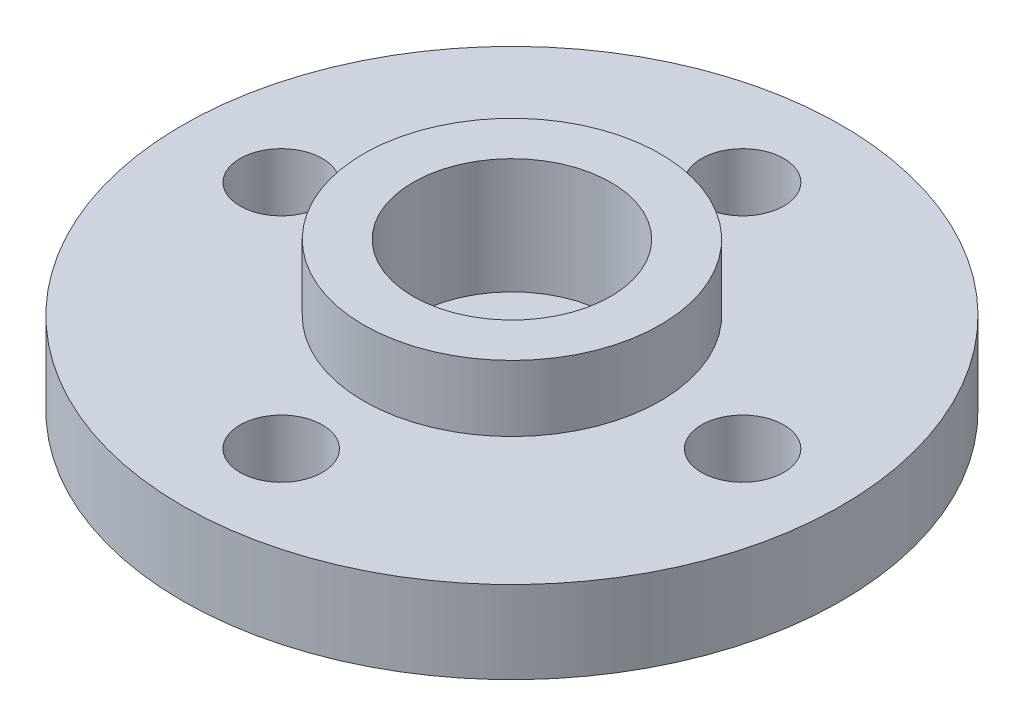
SolidWorks part; units mm, degrees
ref_plane "Top Plane" through (0, 0, 0) normal (0, 0, 1) x (1, 0, 0)
ref_plane "Right Plane" through (0, 0, 0) normal (0, 1, 0) x (1, 0, 0)
ref_plane "Front Plane" through (0, 0, 0) normal (1, 0, 0) x (0, 0, -1)
sketch "Sketch1" plane through (0, 0, 0) normal (1, 0, 0) x (0, 0, -1)
  line L0 (0, 12.5253) -> (0, -12.4242) construction
  line L1 (3, 4.5) -> (3, 1)
  line L2 (1.5, 0) -> (10, 0)
  line L3 (10, 0) -> (10, 2.5)
  line L4 (10, 2.5) -> (4.5, 2.5)
  line L5 (4.5, 2.5) -> (4.5, 4.5)
  line L6 (4.5, 4.5) -> (3, 4.5)
  line L7 (3, 1) -> (1.5, 1)
  line L8 (1.5, 1) -> (1.5, 0)
  point P4 (4.9107, 4.5)
  point P11 (0, 0)
  point P13 (0, 0)
  point P14 (0, 0)
  point P15 (0, 0)
  dimension "D1" = 20
  dimension "D2" = 6
  dimension "D3" = 3
  dimension "D4" = 2.5
  dimension "D5" = 2
  dimension "D6" = 1
  dimension "D7" = 1.5
revolve "Revolve1" add sketch "Sketch1" angle 360 about L0
sketch "Sketch2" plane through (0, 2.5, 0) normal (0, 1, 0) x (1, 0, 0)
  line L0 (0, 7) -> (0, 0) construction
  circle A0 centre (0, 7) radius 1.5 construction
  circle A1 centre (7, 0) radius 1.5 construction
  circle A2 centre (0, -7) radius 1.5 construction
  circle A3 centre (-7, 0) radius 1.5 construction
  circle A4 centre (0, 0) radius 7 construction
  point P13 (0, 0)
  dimension "D1" = 4
  dimension "D2" = 3
  dimension "D3" = 14
hole_wizard "M3 Tapped Hole1" positions "Sketch3" profile "Sketch4" tap size "M3" standard "ISO" end condition through all
sketch "Sketch3" plane through (0, 2.5, 0) normal (0, 1, 0) x (1, 0, 0)
  point P0 (0, 7)
  point P3 (7, 0)
  point P6 (0, -7)
  point P9 (-7, 0)
sketch "Sketch4" plane through (0, 2.5, -7) normal (1, 0, 0) x (0, 0, 1)
  line L0 (0, 0) -> (0, 2.5)
  line L1 (0, 2.5) -> (1.25, 2.5)
  line L2 (1.25, 2.5) -> (1.25, 0)
  line L5 (1.25, 0) -> (0, 0)
  line L11 (0, -6.35) -> (0, 107.95) construction
  dimension "Thru Tap Drill Dia." = 2.5
  dimension "Thru Tap Drill Depth" = 2.5
cosmetic thread "Hole Thread1" parameters "D2"=3
cosmetic thread "Hole Thread2" parameters "D2"=3
cosmetic thread "Hole Thread3" parameters "D2"=3
cosmetic thread "Hole Thread4" parameters "D2"=3
